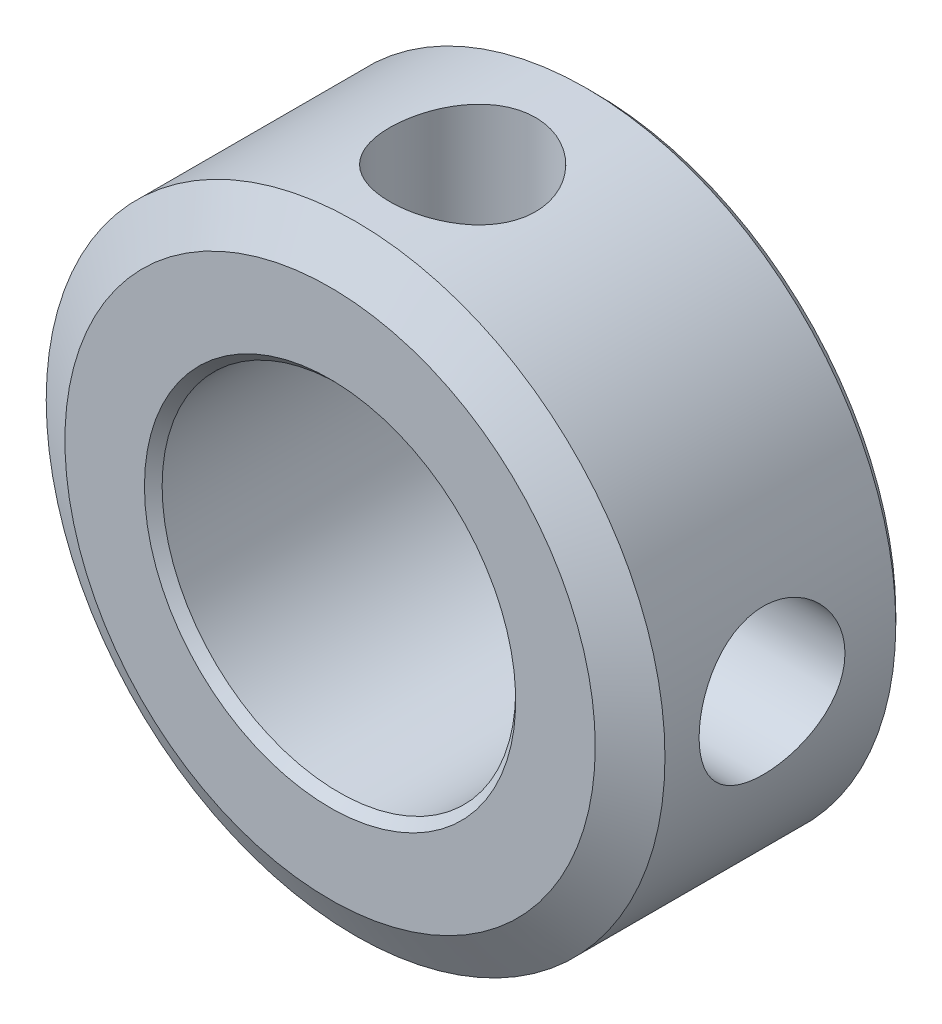
SolidWorks part; units mm, degrees
ref_plane "Front Plane" through (0, 0, 0) normal (0, 0, 1) x (1, 0, 0)
ref_plane "Top Plane" through (0, 0, 0) normal (0, 1, 0) x (1, 0, 0)
ref_plane "Right Plane" through (0, 0, 0) normal (1, 0, 0) x (0, 0, -1)
sketch "Sketch1" plane through (0, 0, 0) normal (1, 0, 0) x (0, 0, -1)
  line L0 (0, 0) -> (6, 0) construction
  line L1 (0, 7) -> (6, 7)
  line L3 (0, 4) -> (6, 4)
  line L4 (6, 7) -> (6, 4)
  line L5 (0, 4) -> (0, 7)
  dimension "D" = 8
  dimension "D1." = 14
  dimension "B" = 6
revolve "Revolve1" add sketch "Sketch1" angle 360 about L0
ref_plane "Plane1" through (0, 7, 0) normal (0, 1, 0) x (1, 0, 0)
hole_wizard "Tapped Hole1" positions "Sketch3" profile "Sketch2" tap size "M4x0.7" standard "JIS"
sketch "Sketch3" plane through (0, 7, 0) normal (0, 1, 0) x (1, 0, 0)
  line L2 (7, 6) -> (-7, 6) construction
  point P0 (0, 3)
sketch "Sketch2" plane through (0, 7, -3) normal (1, 0, 0) x (0, 0, 1)
  line L0 (0, 0) -> (0, 3)
  line L1 (0, 3) -> (1.65, 3)
  line L2 (1.65, 3) -> (1.65, 0)
  line L5 (1.65, 0) -> (0, 0)
  line L11 (0, 0) -> (0, 3) construction
  dimension "Thru Tap Drill Dia." = 3.3
  dimension "Thru Tap Drill Depth" = 3
cosmetic thread "Hole Thread2"
pattern_circular "CirPattern1" count 2 every 90 about axis through (0, 0, 0) along (0, 0, 1) of "Tapped Hole1"
chamfer "Chamfer1" distance 0.2 3 edges at (7, 0, -6) (4, 0, 0) (4, 0, -6)
sketch "Sketch4" plane through (0, 0, 0) normal (1, 0, 0) x (0, 0, -1)
  line L1 (0.5774, 7) -> (0, 6)
  line L3 (0, 7) -> (6, 7) construction
  line L4 (0.5774, 7) -> (0, 7)
  line L5 (0, 0) -> (6, 0) construction
  line L6 (6, -7) -> (6, 7) construction
  line L7 (0, 4) -> (0, 7) construction
  line L8 (0, 7) -> (0, 6)
  dimension "D1_s" = 12
  dimension "D1" = 30
revolve "Cut-Revolve1" cut sketch "Sketch4" angle 360 about L5
sketch "Sketch5" [suppressed] plane through (0, 0, 0) normal (1, 0, 0) x (0, 0, -1)
  line L0 (0, 5.5) -> (0, 5)
  line L1 (0, 5.5) -> (0, -5.5) construction
  line L2 (0, 5) -> (0.2887, 5.5)
  line L5 (0, 0) -> (8, 0) construction
  line L6 (8, -5.3) -> (8, 5.3) construction
  line L7 (0.2887, 5.5) -> (0, 5.5)
  dimension "D1" = 30
  dimension "D1_s" = 12
  dimension "D1." = 14
revolve "Cut-Revolve2" [suppressed] cut sketch "Sketch5" angle 360 about L5
equation "\"D1@Sketch3\"= \"B@Sketch1\" / 2"
equation "\"Cut-Revolve1\" = if ( \"D1.@Sketch1\" = \"D1_s@Sketch4\" , \"suppressed\" , \"unsuppressed\" )"
equation "\"Plane dim\"= \"D1.@Sketch1\" * 0.5"
